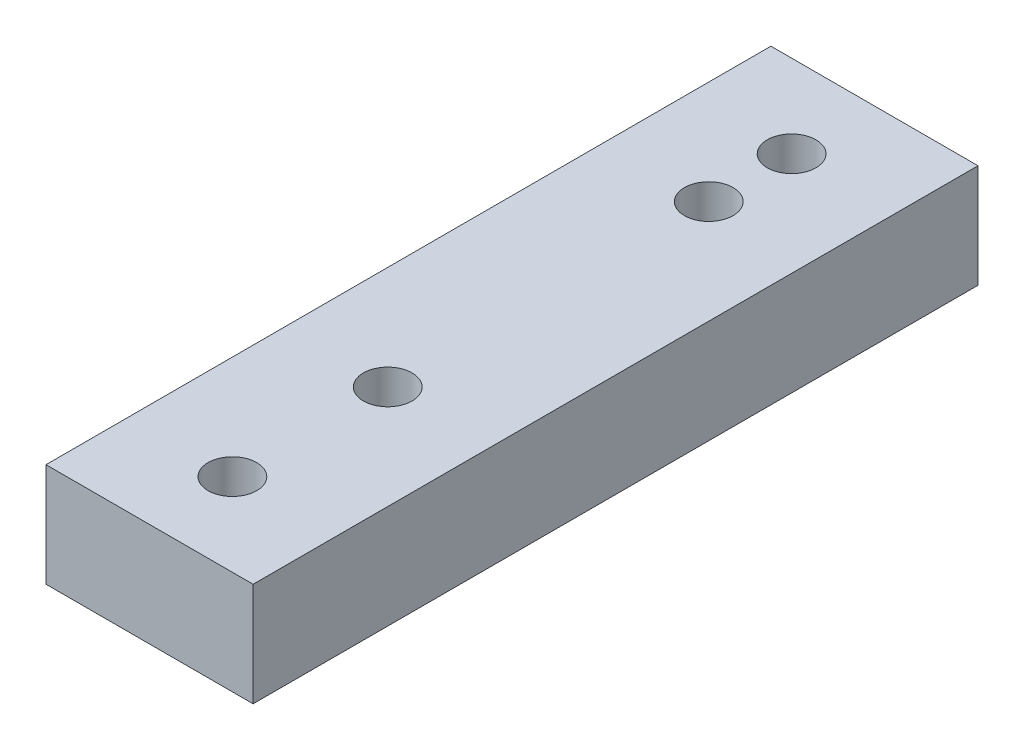
SolidWorks part; units mm, degrees
ref_plane "Front Plane" through (0, 0, 0) normal (0, 0, 1) x (1, 0, 0)
ref_plane "Top Plane" through (0, 0, 0) normal (0, 1, 0) x (1, 0, 0)
ref_plane "Right Plane" through (0, 0, 0) normal (1, 0, 0) x (0, 0, -1)
sketch "Sketch1" plane through (0, 0, 0) normal (0, 1, 0) x (1, 0, 0)
  line L1 (0, 0) -> (20, 0)
  line L2 (0, 0) -> (0, 70)
  line L3 (0, 70) -> (20, 70)
  line L4 (20, 0) -> (20, 70)
  circle A0 centre (10, 62) radius 2.35
  circle A1 centre (10, 54) radius 2.35
  circle A2 centre (10, 23) radius 2.35
  circle A3 centre (10, 8) radius 2.35
  dimension "D3" = 4.7
  dimension "D4" = 4.7
  dimension "D7" = 4.7
  dimension "D9" = 4.7
  dimension "D1" = 20
  dimension "D2" = 70
  dimension "D5" = 8
  dimension "D6" = 8
  dimension "D8" = 15
  dimension "D10" = 8
extrude "Boss-Extrude1" add sketch "Sketch1" along normal blind 10
